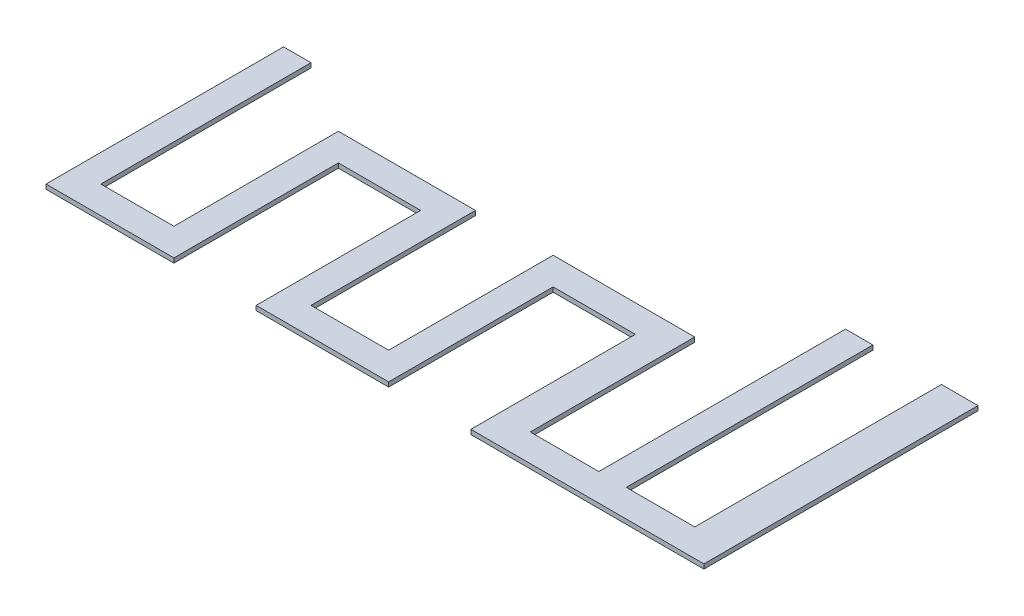
SolidWorks part; units mm, degrees
material "E-Glass Fiber"
ref_plane "Front Plane" through (0, 0, 0) normal (0, 0, 1) x (1, 0, 0)
ref_plane "Top Plane" through (0, 0, 0) normal (0, 1, 0) x (1, 0, 0)
ref_plane "Right Plane" through (0, 0, 0) normal (1, 0, 0) x (0, 0, -1)
sketch "Sketch1" plane through (0, 0, 0) normal (0, 1, 0) x (1, 0, 0)
  line L0 (-29.337, 0) -> (29.337, 0) construction
  line L1 (0, 0) -> (-53.34, 0)
  line L2 (0, 0) -> (0, 66.04)
  line L3 (-5.08, 68.58) -> (-37.846, 68.58)
  line L4 (-53.34, 0) -> (-53.34, 66.04)
  line L5 (-53.34, 66.04) -> (-40.386, 66.04)
  line L6 (-40.386, 66.04) -> (-37.846, 68.58)
  line L7 (-5.08, 68.58) -> (-2.54, 66.04)
  line L8 (-2.54, 66.04) -> (0, 66.04)
  circle A0 centre (-7.62, 66.04) radius 1.5875
  circle A1 centre (-35.56, 66.04) radius 1.5875
  circle A2 centre (-2.54, 13.97) radius 1.5875
  circle A3 centre (-50.8, 15.24) radius 1.5875
  dimension "D8" = 3.175
  dimension "D1" = 68.58
  dimension "D2" = 53.34
  dimension "D3" = 66.04
  dimension "D4" = 2.54
  dimension "D5" = 45
  dimension "D6" = 45
  dimension "D7" = 40.386
  dimension "D9" = 66.04
  dimension "D10" = 35.56
  dimension "D11" = 7.62
  dimension "D12" = 13.97
  dimension "D13" = 2.54
  dimension "D14" = 15.24
  dimension "D15" = 50.8
extrude "Boss-Extrude1" add sketch "Sketch1" against normal blind 1.65
sketch "Sketch2" plane through (0, 0, 0) normal (0, 1, 0) x (1, 0, 0)
  line L0 (0, -0.9625) -> (0, 0.9625) construction
  line L1 (-0.9625, 0) -> (0.9625, 0) construction
  circle A0 centre (-2.54, 27.94) radius 0.4
  dimension "D1" = 0.8
  dimension "D2" = 2.54
  dimension "D3" = 27.94
extrude "Cut-Extrude1" cut sketch "Sketch2" against normal blind 1.65
sketch "Sketch3" plane through (0, 0, 0) normal (0, 1, 0) x (1, 0, 0)
  line L0 (0, -0.9625) -> (0, 0.9625) construction
  line L1 (-0.9625, 0) -> (0.9625, 0) construction
  circle A0 centre (-50.8, 18.796) radius 0.4
  dimension "D2" = 0.8
  dimension "D1" = 50.8
  dimension "D3" = 18.796
extrude "Cut-Extrude2" cut sketch "Sketch3" against normal blind 1.65
pattern_linear "LPattern1" count 15 spacing 2.54 along (0, 0, -1) skipping (8, 0) of "Cut-Extrude1"
sketch "Sketch4" plane through (0, 0, 0) normal (0, 1, 0) x (1, 0, 0)
  line L0 (-0.9625, 0) -> (0.9625, 0) construction
  line L1 (0, -0.9625) -> (0, 0.9625) construction
  circle A0 centre (-50.8, 45.72) radius 0.4
  dimension "D3" = 0.8
  dimension "D1" = 45.72
  dimension "D2" = 50.8
extrude "Cut-Extrude3" cut sketch "Sketch4" against normal blind 1.65
pattern_linear "LPattern2" count 10 spacing 2.54 along (0, 0, -1) of "Cut-Extrude2"
sketch "Sketch5" [suppressed] plane through (0, 0, 0) normal (0, 1, 0) x (1, 0, 0)
  line L0 (-27.89, 66.18) -> (-27.89, 63.64) construction
  line L1 (-30.43, 66.18) -> (-25.35, 66.18) construction
  line L2 (-30.43, 66.18) -> (-30.43, 63.64) construction
  line L3 (-30.43, 63.64) -> (-25.35, 63.64) construction
  line L4 (-25.35, 66.18) -> (-25.35, 63.64) construction
  line L5 (-0.9625, 0) -> (0.9625, 0) construction
  line L6 (0, -0.9625) -> (0, 0.9625) construction
  circle A0 centre (-30.43, 66.18) radius 0.4
  circle A1 centre (-27.89, 66.18) radius 0.4
  circle A2 centre (-25.35, 66.18) radius 0.4
  circle A3 centre (-25.35, 63.64) radius 0.4
  circle A4 centre (-27.89, 63.64) radius 0.4
  circle A5 centre (-30.43, 63.64) radius 0.4
  circle A6 centre (-47.498, 15.748) radius 0.4
  circle A7 centre (-47.498, 18.288) radius 0.4
  circle A8 centre (-47.498, 20.828) radius 0.4
  circle A9 centre (-44.958, 20.828) radius 0.4
  circle A10 centre (-44.958, 18.288) radius 0.4
  circle A11 centre (-44.958, 15.748) radius 0.4
  dimension "D4" = 0.8
  dimension "D1" = 2.54
  dimension "D2" = 2.54
  dimension "D3" = 2.54
  dimension "D5" = 63.64
  dimension "D6" = 30.43
  dimension "D7" = 2.54
  dimension "D8" = 2.54
  dimension "D9" = 2.54
  dimension "D12" = 47.498
  dimension "D13" = 15.748
sketch "草图1" plane through (0, 0, 0) normal (0, 1, 0) x (1, 0, 0)
  line L0 (-37.34, -11.7574) -> (-37.34, -16.9574)
  line L2 (-37.34, -16.9574) -> (-34.54, -16.9574)
  line L3 (-34.54, -16.9574) -> (-34.54, -13.3574)
  line L4 (-34.54, -13.3574) -> (-32.74, -13.3574)
  line L5 (-32.74, -13.3574) -> (-32.74, -16.9574)
  line L6 (-32.74, -16.9574) -> (-29.84, -16.9574)
  line L7 (-29.84, -16.9574) -> (-29.84, -13.3574)
  line L8 (-29.84, -13.3574) -> (-28.04, -13.3574)
  line L9 (-28.04, -13.3574) -> (-28.04, -16.9574)
  line L10 (-28.04, -16.9574) -> (-22.94, -16.9574)
  line L11 (-22.94, -16.9574) -> (-22.94, -10.9574)
  line L12 (-22.94, -10.9574) -> (-23.74, -10.9574)
  line L13 (-23.74, -10.9574) -> (-23.74, -16.3574)
  line L14 (-23.74, -16.3574) -> (-25.24, -16.3574)
  line L15 (-25.24, -16.3574) -> (-25.24, -10.9574)
  line L16 (-25.24, -10.9574) -> (-25.84, -10.9574)
  line L17 (-25.84, -10.9574) -> (-25.84, -16.3574)
  line L18 (-25.84, -16.3574) -> (-27.34, -16.3574)
  line L19 (-27.34, -16.3574) -> (-27.34, -12.7574)
  line L20 (-27.34, -12.7574) -> (-30.44, -12.7574)
  line L21 (-30.44, -12.7574) -> (-30.44, -16.3574)
  line L22 (-30.44, -16.3574) -> (-32.14, -16.3574)
  line L23 (-32.14, -16.3574) -> (-32.14, -12.7574)
  line L24 (-32.14, -12.7574) -> (-35.14, -12.7574)
  line L25 (-35.14, -12.7574) -> (-35.14, -16.3574)
  line L26 (-35.14, -16.3574) -> (-36.74, -16.3574)
  line L27 (-36.74, -16.3574) -> (-36.74, -11.7574)
  line L28 (-36.74, -11.7574) -> (-37.34, -11.7574)
  line L29 (-53.34, 66.04) -> (-53.34, 0) construction
  dimension "D1" = 0.6
  dimension "D2" = 0.6
  dimension "D3" = 0.6
  dimension "D4" = 0.6
  dimension "D5" = 0.6
  dimension "D6" = 0.6
  dimension "D7" = 0.6
  dimension "D8" = 0.6
  dimension "D9" = 0.7
  dimension "D10" = 0.6
  dimension "D11" = 0.6
  dimension "D12" = 0.8
  dimension "D13" = 1.6
  dimension "D14" = 1.8
  dimension "D15" = 1.7
  dimension "D16" = 1.8
  dimension "D17" = 1.5
  dimension "D18" = 1.5
  dimension "D19" = 5.2
  dimension "D20" = 3.6
  dimension "D21" = 6
  dimension "D22" = 16
extrude "凸台-拉伸1" add sketch "草图1" along normal blind 0.1 separate body
sketch "草图2" plane through (0, 0, 0) normal (0, 1, 0) x (1, 0, 0)
  line L1 (-59.7064, -7.2371) -> (11.9897, -7.2371)
  line L2 (-59.7064, -7.2371) -> (-59.7064, 76.6718)
  line L3 (-59.7064, 76.6718) -> (11.9897, 76.6718)
  line L4 (11.9897, -7.2371) -> (11.9897, 76.6718)
extrude "切除-拉伸1" cut sketch "草图2" against normal through all
equation "\"D13@Sketch5\"=0.001*25.4*620"
